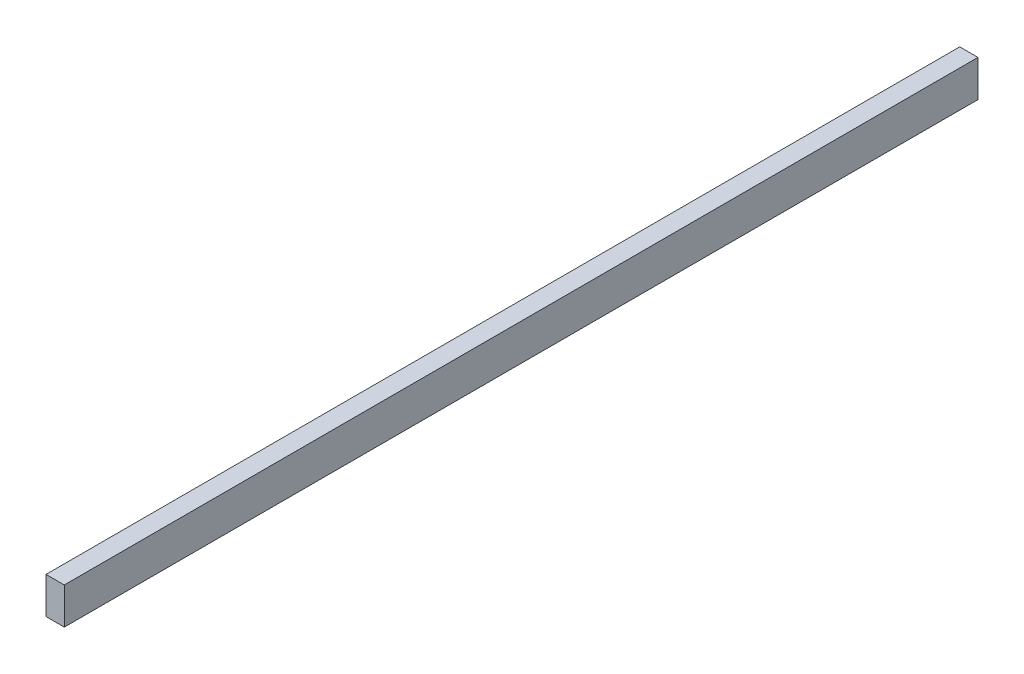
SolidWorks part; units mm, degrees
material "S355 verification"
ref_plane "Front Plane" through (0, 0, 0) normal (0, 0, 1) x (1, 0, 0)
ref_plane "Top Plane" through (0, 0, 0) normal (0, 1, 0) x (1, 0, 0)
ref_plane "Right Plane" through (0, 0, 0) normal (1, 0, 0) x (0, 0, -1)
sketch "Sketch1" plane through (0, 0, 0) normal (0, 0, 1) x (1, 0, 0)
  line L1 (-20, -40) -> (20, -40)
  line L2 (-20, -40) -> (-20, 40)
  line L3 (-20, 40) -> (20, 40)
  line L4 (20, -40) -> (20, 40)
  line L5 (-20, -40) -> (20, 40) construction
  line L6 (-20, 40) -> (20, -40) construction
  point P0 (0, 0)
extrude "Boss-Extrude1" add sketch "Sketch1" along normal blind 2000
